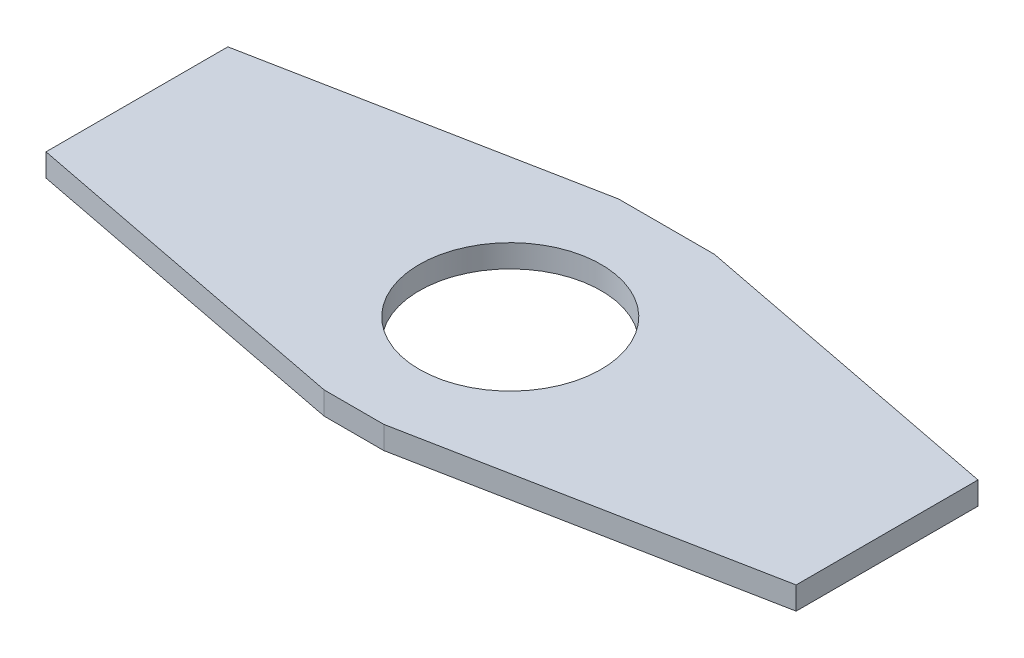
SolidWorks part; units mm, degrees
ref_plane "Front Plane" through (0, 0, 0) normal (0, 0, 1) x (1, 0, 0)
ref_plane "Top Plane" through (0, 0, 0) normal (0, 1, 0) x (1, 0, 0)
ref_plane "Right Plane" through (0, 0, 0) normal (1, 0, 0) x (0, 0, -1)
sketch "Sketch2" plane through (0, 0, 0) normal (0, 1, 0) x (1, 0, 0)
  line L0 (-66, 16.3086) -> (-66, -15.6914)
  line L1 (-66, -15.6914) -> (-5.25, -27.5)
  line L6 (8.4253, 27.5) -> (-8.4253, 27.5)
  line L7 (-8.4253, 27.5) -> (-66, 16.3086)
  line L8 (0, -654.2456) -> (0, 32058.0366) construction
  line L9 (66, -15.6914) -> (5.25, -27.5)
  line L10 (8.4253, 27.5) -> (66, 16.3086)
  line L11 (66, 16.3086) -> (66, -15.6914)
  line L12 (-5.25, -27.5) -> (5.25, -27.5)
  circle A0 centre (0, 0) radius 16
  point P16 (0, -31)
  point P18 (0, 27.5)
  dimension "D7" = 32
  dimension "D1" = 55
  dimension "D2" = 27.5
  dimension "D3" = 10.5
  dimension "D4" = 169
  dimension "D5" = 169
  dimension "D6" = 32
  dimension "D8" = 66
extrude "Boss-Extrude1" add sketch "Sketch2" along normal blind 4
